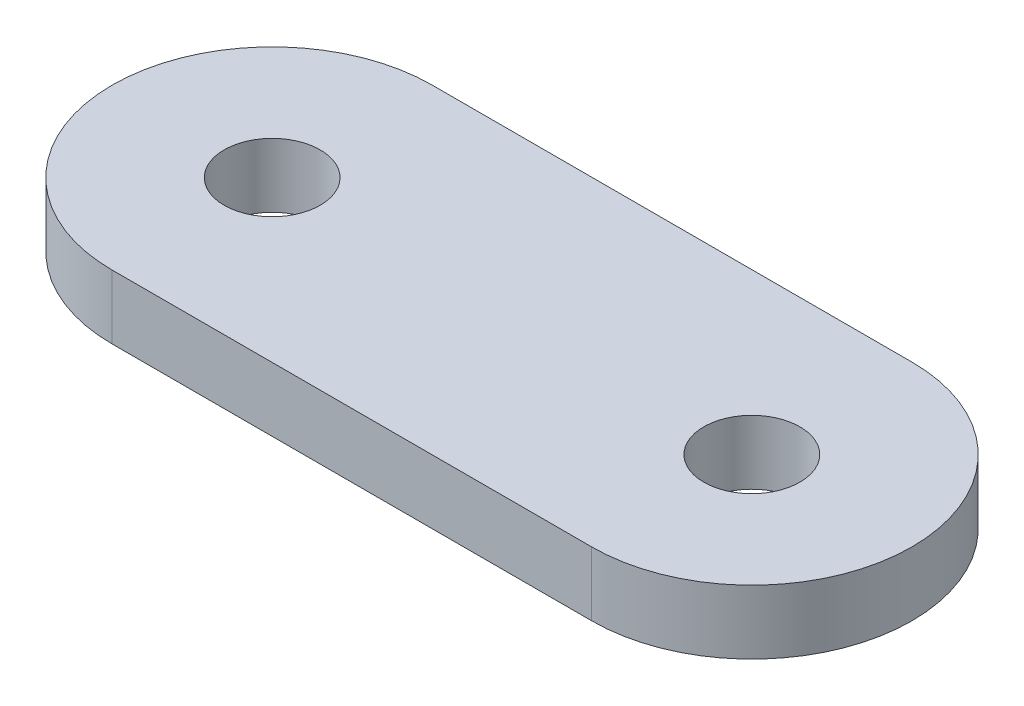
SolidWorks part; units mm, degrees
ref_plane "前视基准面" through (0, 0, 0) normal (0, 0, 1) x (1, 0, 0)
ref_plane "上视基准面" through (0, 0, 0) normal (0, 1, 0) x (1, 0, 0)
ref_plane "右视基准面" through (0, 0, 0) normal (1, 0, 0) x (0, 0, -1)
sketch "Sketch1" plane through (0, 0, 0) normal (0, 1, 0) x (1, 0, 0)
  line L0 (7.49, 0) -> (-7.49, 0) construction
  line L1 (-7.49, 5) -> (7.49, 5)
  line L2 (-7.49, -5) -> (7.49, -5)
  arc A2 (-7.49, 5) -> (-7.49, -5) centre (-7.49, 0) ccw
  arc A3 (7.49, -5) -> (7.49, 5) centre (7.49, 0) ccw
  circle A4 centre (7.49, 0) radius 1.5
  circle A5 centre (-7.49, 0) radius 1.5
  point P4 (0, 0)
  dimension "D1" = 3
  dimension "D3" = 14.98
  dimension "D4" = 10
  dimension "D5" = 10
  dimension "D2" = 3
extrude "Boss-Extrude1" add sketch "Sketch1" along normal blind 2
